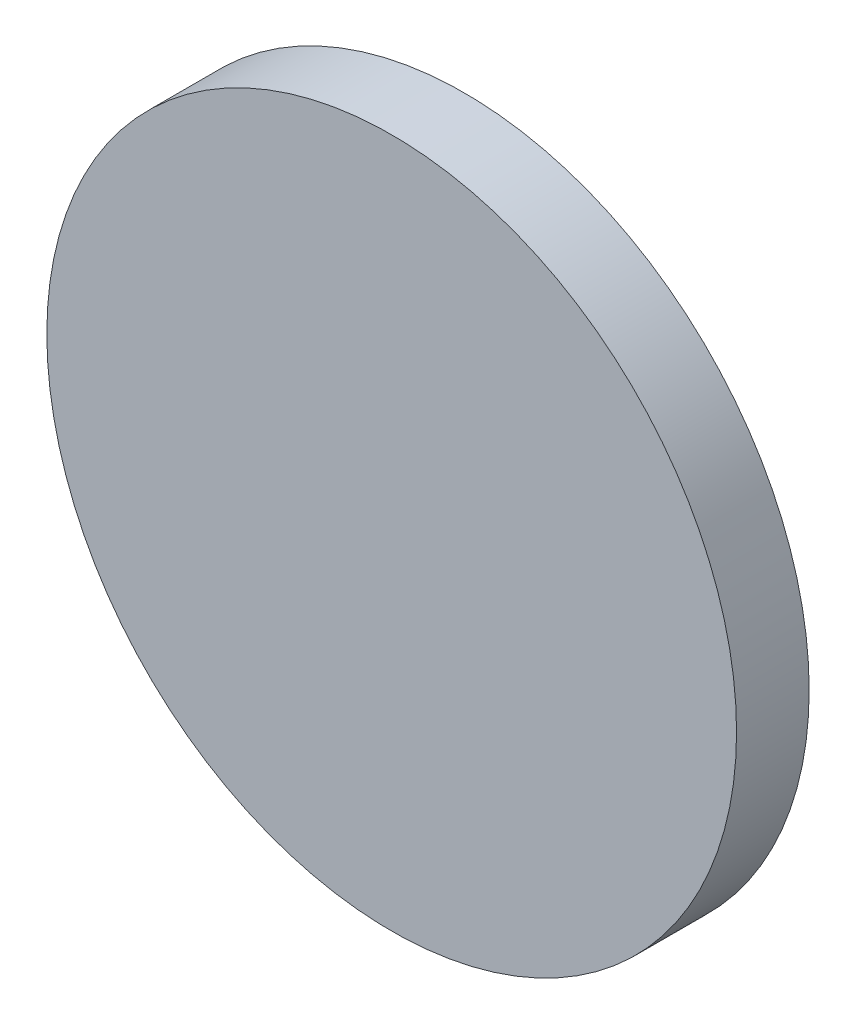
SolidWorks part; units mm, degrees
material "Vidrio"
ref_plane "Alzado" through (0, 0, 0) normal (0, 0, 1) x (1, 0, 0)
ref_plane "Planta" through (0, 0, 0) normal (0, 1, 0) x (1, 0, 0)
ref_plane "Vista lateral" through (0, 0, 0) normal (1, 0, 0) x (0, 0, -1)
sketch "Croquis1" plane through (0, 0, 0) normal (0, 0, 1) x (1, 0, 0)
  circle A0 centre (0, 0) radius 9.5
  dimension "D1" = 19
extrude "Saliente-Extruir1" add sketch "Croquis1" along normal blind 2
